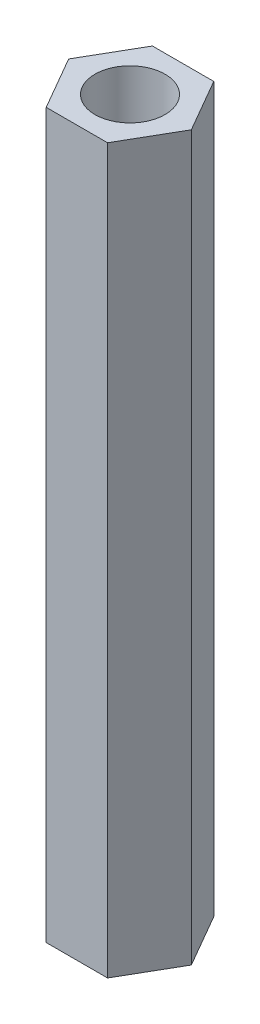
SolidWorks part; units mm, degrees
material "黄铜"
ref_plane "前视基准面" through (0, 0, 0) normal (0, 0, 1) x (1, 0, 0)
ref_plane "上视基准面" through (0, 0, 0) normal (0, 1, 0) x (1, 0, 0)
ref_plane "右视基准面" through (0, 0, 0) normal (1, 0, 0) x (0, 0, -1)
sketch "草图1" plane through (0, 0, 0) normal (0, 1, 0) x (1, 0, 0)
  line L1 (2.7135, 0) -> (1.3568, 2.35)
  line L2 (1.3568, 2.35) -> (-1.3568, 2.35)
  line L3 (-1.3568, 2.35) -> (-2.7135, 0)
  line L4 (-2.7135, 0) -> (-1.3568, -2.35)
  line L5 (-1.3568, -2.35) -> (1.3568, -2.35)
  line L6 (1.3568, -2.35) -> (2.7135, 0)
  circle A0 centre (0, 0) radius 1.55
  circle A1 centre (0, 0) radius 2.35 construction
  dimension "D1" = 3.1
  dimension "D2" = 4.7
extrude "凸台-拉伸1" add sketch "草图1" along normal blind 32
